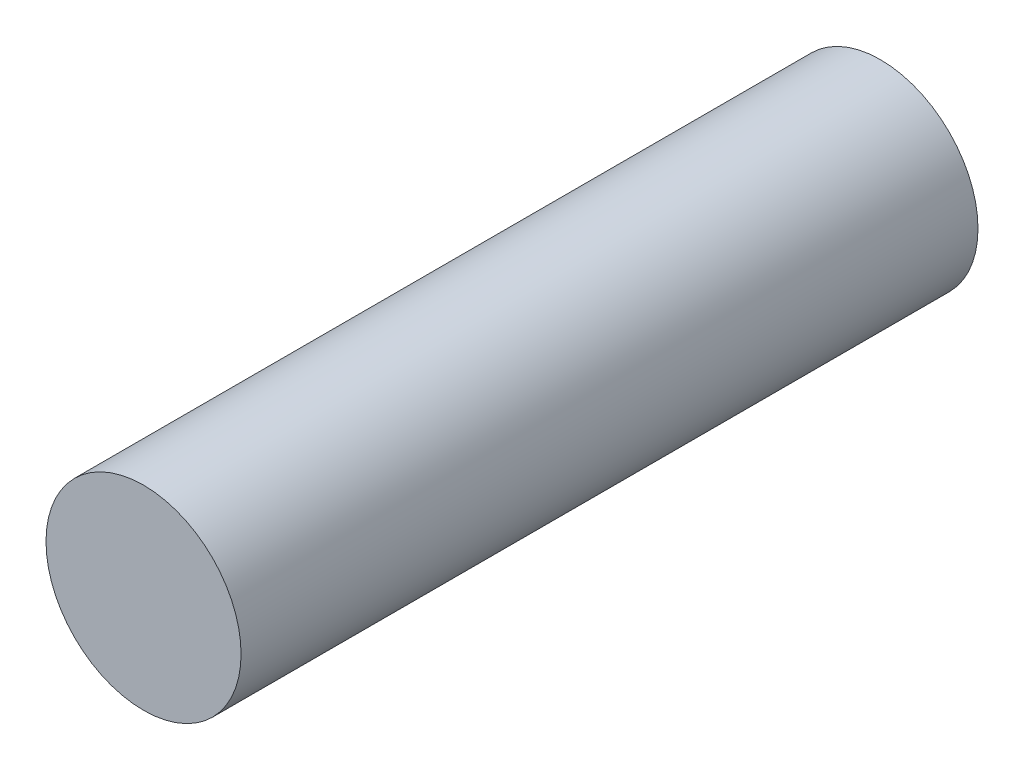
SolidWorks part; units mm, degrees
ref_plane "Front Plane" through (0, 0, 0) normal (0, 0, 1) x (1, 0, 0)
ref_plane "Top Plane" through (0, 0, 0) normal (0, 1, 0) x (1, 0, 0)
ref_plane "Right Plane" through (0, 0, 0) normal (1, 0, 0) x (0, 0, -1)
sketch "Sketch1" plane through (0, 0, 0) normal (0, 0, 1) x (1, 0, 0)
  circle A0 centre (0, 0) radius 2.25
  dimension "D1" = 4.5
extrude "Boss-Extrude1" add sketch "Sketch1" along normal blind 17
sketch "Sketch2" plane through (0, 0, 0) normal (0, 0, 1) x (1, 0, 0)
  circle A0 centre (0, 0) radius 3 construction
